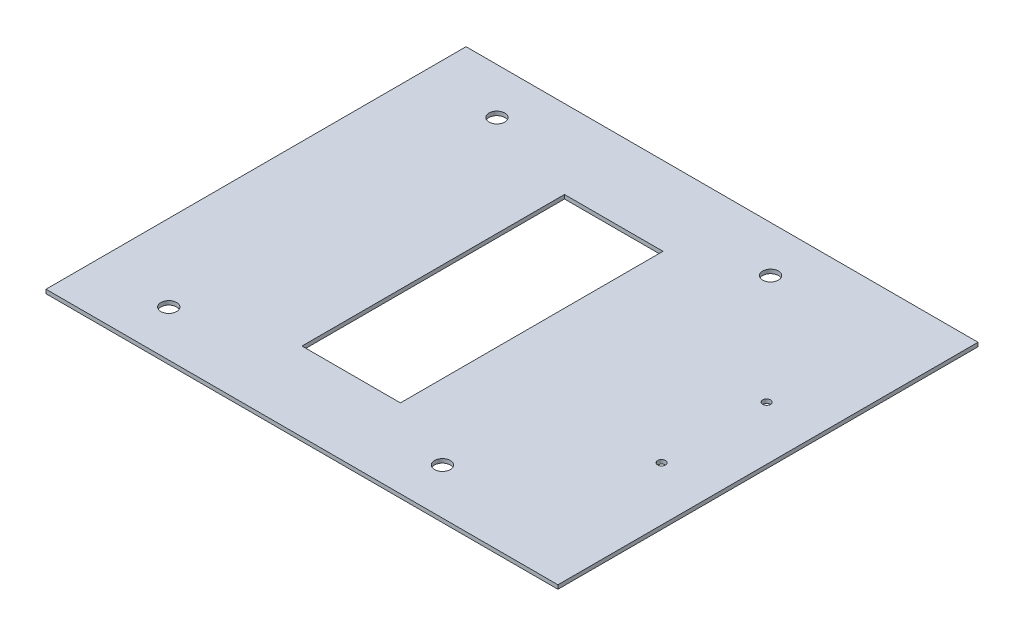
SolidWorks part; units mm, degrees
material "PW80:Mi:0:41:Ar:0:-1:C1:1:2:3:Re:15:"
ref_plane "Plan1" through (0, 0, 0) normal (0, 0, 1) x (1, 0, 0)
ref_plane "Plan2" through (0, 0, 0) normal (0, 1, 0) x (1, 0, 0)
ref_plane "Plan3" through (0, 0, 0) normal (1, 0, 0) x (0, 0, -1)
sketch "Esquisse1" plane through (0, 0, 0) normal (0, 1, 0) x (1, 0, 0)
  line L1 (0, 0) -> (390, 0)
  line L2 (0, 0) -> (0, 320)
  line L3 (0, 320) -> (390, 320)
  line L4 (390, 0) -> (390, 320)
extrude "Base-Extrusion" add sketch "Esquisse1" along normal blind 3
sketch "Esquisse2" plane through (0, 3, 0) normal (0, 1, 0) x (-1, 0, 0)
  line L1 (-135, -60) -> (-210, -60)
  line L2 (-135, -60) -> (-135, -260)
  line L3 (-135, -260) -> (-210, -260)
  line L4 (-210, -60) -> (-210, -260)
extrude "Enlèv. mat.-Extru.1" cut sketch "Esquisse2" against normal blind 4
sketch "Esquisse3" plane through (0, 3, 0) normal (0, 1, 0) x (-1, 0, 0)
  circle A0 centre (-267, -285) radius 6
  circle A1 centre (-58.5, -285) radius 6
  circle A2 centre (-267, -35) radius 6
  circle A3 centre (-58.5, -35) radius 6
extrude "Enlèv. mat.-Extru.2" cut sketch "Esquisse3" against normal blind 4
sketch "Esquisse4" plane through (0, 3, 0) normal (0, 1, 0) x (-1, 0, 0)
  circle A0 centre (-349, -200) radius 3
  circle A1 centre (-349, -120) radius 3
extrude "Enlèv. mat.-Extru.3" cut sketch "Esquisse4" against normal blind 10
